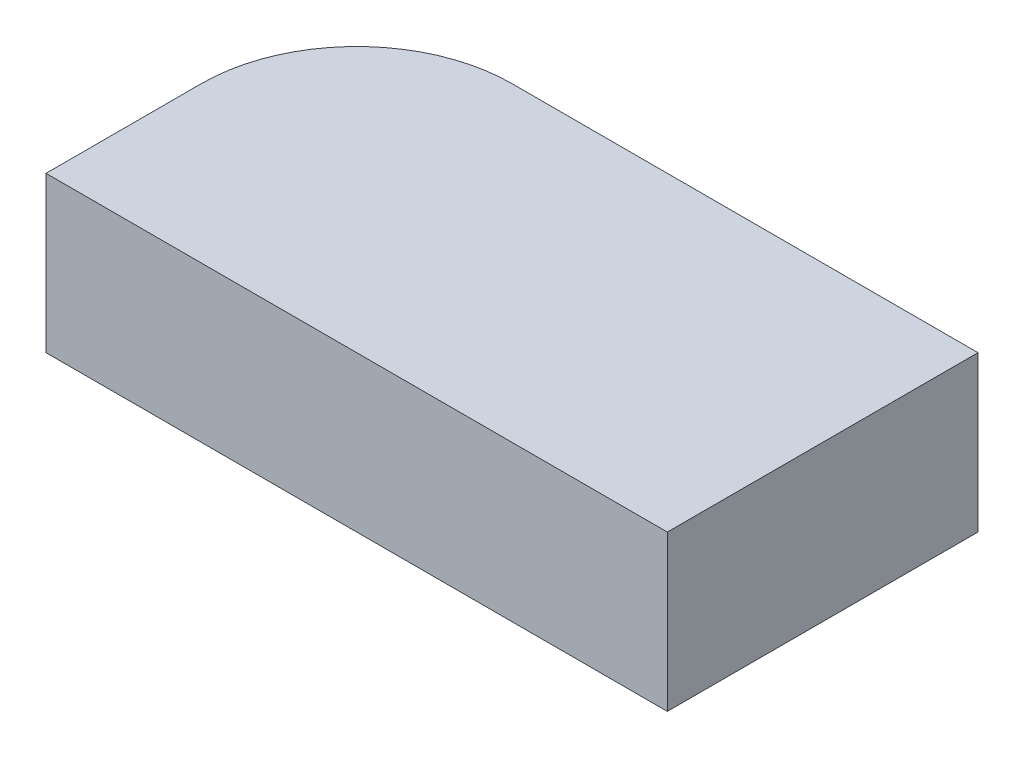
SolidWorks part; units mm, degrees
ref_plane "Přední rovina" through (0, 0, 0) normal (0, 0, 1) x (1, 0, 0)
ref_plane "Horní rovina" through (0, 0, 0) normal (0, 1, 0) x (1, 0, 0)
ref_plane "Pravá rovina" through (0, 0, 0) normal (1, 0, 0) x (0, 0, -1)
sketch "Sketch1" plane through (0, 0, 0) normal (0, 1, 0) x (1, 0, 0)
  line L0 (0, 0) -> (60, 0)
  line L1 (-20, -40) -> (60, -40)
  line L2 (-20, -40) -> (-20, -20)
  line L4 (60, -40) -> (60, 0)
  arc A0 (-20, -20) -> (0, 0) centre (0, -20) cw
  point P1 (2.6369, -10.8234)
  dimension "D1" = 20
  dimension "D2" = 80
  dimension "D3" = 40
extrude "Boss-Extrude1" add sketch "Sketch1" along normal blind 20
equation "\"R\" = 20'Radius"
equation "\"H\"= 20'Extrude height"
equation "\"D1@Boss-Extrude1\"=\"H\""
equation "\"D2@Sketch1\"=\"R\"*4"
equation "\"D3@Sketch1\"=\"R\"*2mm"
equation "\"D1@Sketch1\"=\"R\""
